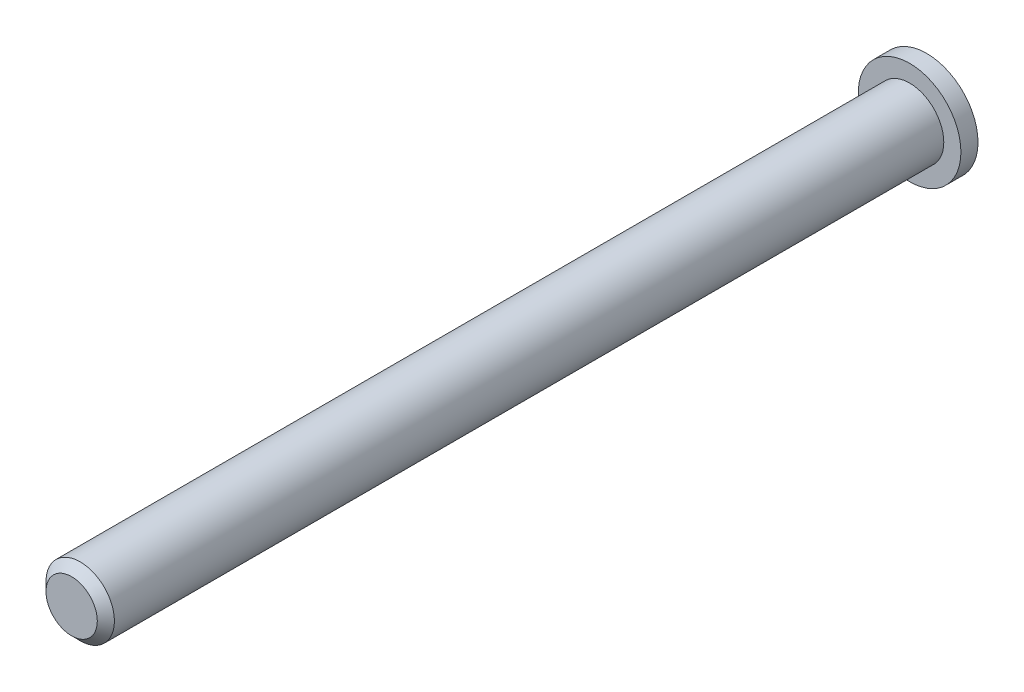
SolidWorks part; units mm, degrees
ref_plane "Front Plane" through (0, 0, 0) normal (0, 0, 1) x (1, 0, 0)
ref_plane "Top Plane" through (0, 0, 0) normal (0, 1, 0) x (1, 0, 0)
ref_plane "Right Plane" through (0, 0, 0) normal (1, 0, 0) x (0, 0, -1)
sketch "Sketch1" plane through (0, 0, 0) normal (0, 0, 1) x (1, 0, 0)
  circle A0 centre (0, 0) radius 1.5
  dimension "D1" = 3
extrude "Boss-Extrude1" add sketch "Sketch1" along normal blind 0.5
sketch "Sketch2" plane through (0, 0, 0.5) normal (0, 0, 1) x (1, 0, 0)
  circle A0 centre (0, 0) radius 1
  dimension "D1" = 2
extrude "Boss-Extrude2" add sketch "Sketch2" along normal blind 24.5
chamfer "Chamfer1" distance 0.25 angle 45 1 edges at (1, 0, 25)
